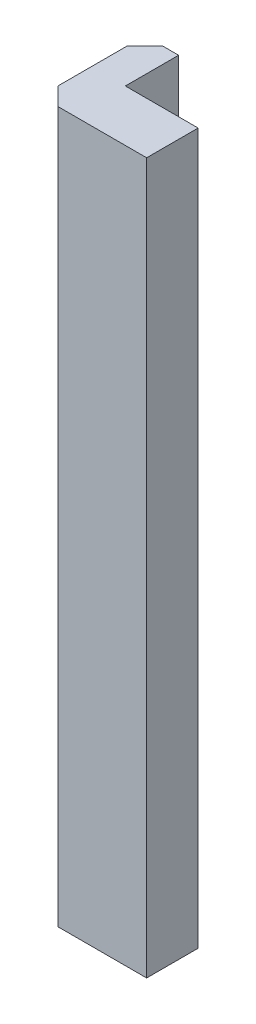
SolidWorks part; units mm, degrees
ref_plane "Front Plane" through (0, 0, 0) normal (0, 0, 1) x (1, 0, 0)
ref_plane "Top Plane" through (0, 0, 0) normal (0, 1, 0) x (1, 0, 0)
ref_plane "Right Plane" through (0, 0, 0) normal (1, 0, 0) x (0, 0, -1)
sketch "Sketch1" plane through (0, 0, 0) normal (0, 1, 0) x (1, 0, 0)
  line L0 (0, -2) -> (1, -3)
  line L2 (0, 0) -> (0, 1.9)
  line L3 (1, 2.9) -> (1.9, 2.9)
  line L4 (1.9, -0.1) -> (1.9, 2.9)
  line L5 (1.9, -0.1) -> (6, -0.1)
  line L6 (0, 0) -> (0, -2)
  line L7 (1, -3) -> (6, -3)
  line L8 (6, -0.1) -> (6, -3)
  line L9 (0, 1.9) -> (1, 2.9)
  point P2 (0, 2.9)
  point P5 (0, -3)
  dimension "D1" = 1.9
  dimension "D2" = 3
  dimension "D3" = 2.9
  dimension "D4" = 6
extrude "Boss-Extrude1" add sketch "Sketch1" along normal blind 40
